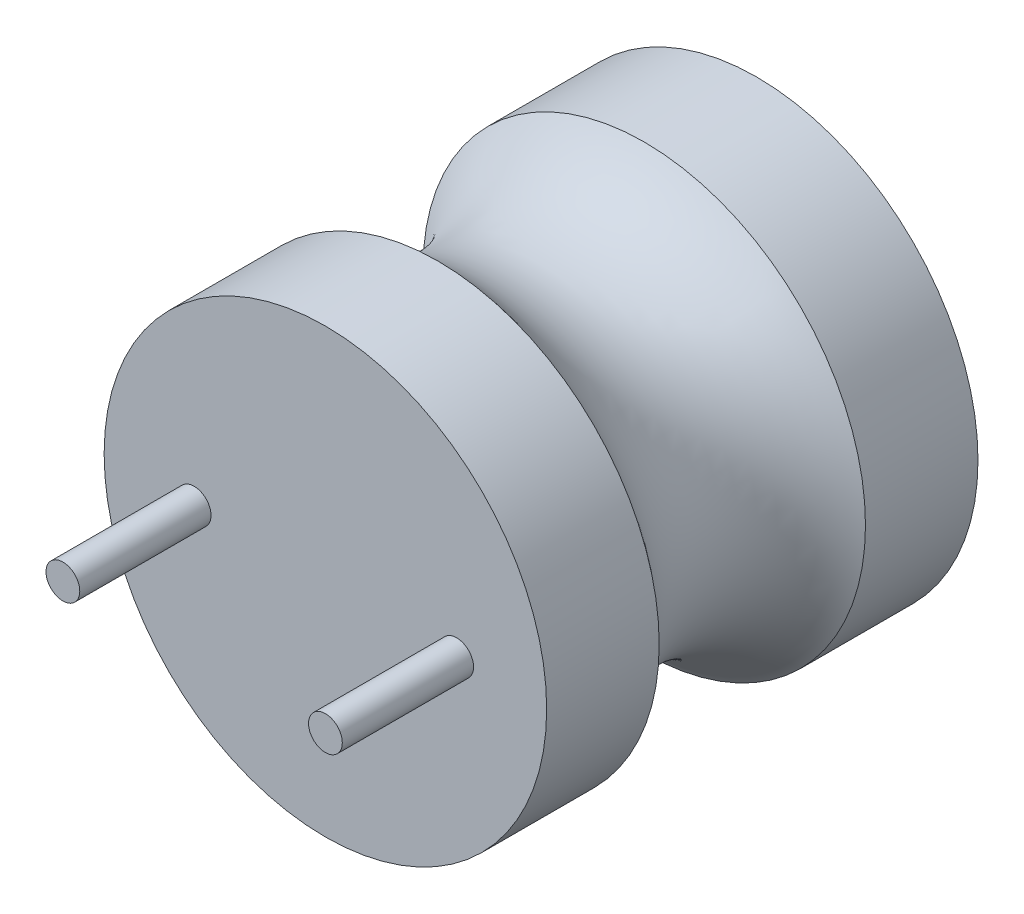
SolidWorks part; units mm, degrees
ref_plane "Спереди" through (0, 0, 0) normal (0, 0, 1) x (1, 0, 0)
ref_plane "Сверху" through (0, 0, 0) normal (0, 1, 0) x (1, 0, 0)
ref_plane "Справа" through (0, 0, 0) normal (1, 0, 0) x (0, 0, -1)
sketch "Эскиз1" plane through (0, 0, 0) normal (0, 1, 0) x (1, 0, 0)
  line L0 (0, 0) -> (0, 11.5)
  line L1 (0, 11.5) -> (-5.9, 11.5)
  line L2 (-5.9, 11.5) -> (-5.9, 8.5)
  line L3 (0, 0) -> (-5.9, 0)
  line L4 (-5.9, 0) -> (-5.9, 3)
  arc A2 (-5.9, 3) -> (-5.9, 8.5) centre (-7.9009, 5.75) ccw
  point P7 (0, 0)
  point P11 (-4.5, 5.75)
  dimension "D1" = 11.5
  dimension "D2" = 5.9
  dimension "D3" = 5.9
  dimension "D4" = 3
  dimension "D5" = 3
  dimension "D6" = 5.75
  dimension "D7" = 4.5
revolve "Повернуть1" add sketch "Эскиз1" angle 360 about L0
sketch "Эскиз2" plane through (0, 0, 0) normal (0, 0, 1) x (1, 0, 0)
  circle A0 centre (-3.5, 0) radius 0.45
  circle A1 centre (3.5, 0) radius 0.45
  point P4 (0, 0)
  dimension "D3" = 0.9
  dimension "D1" = 3.5
  dimension "D2" = 3.5
extrude "Бобышка-Вытянуть1" add sketch "Эскиз2" along normal blind 3.5
